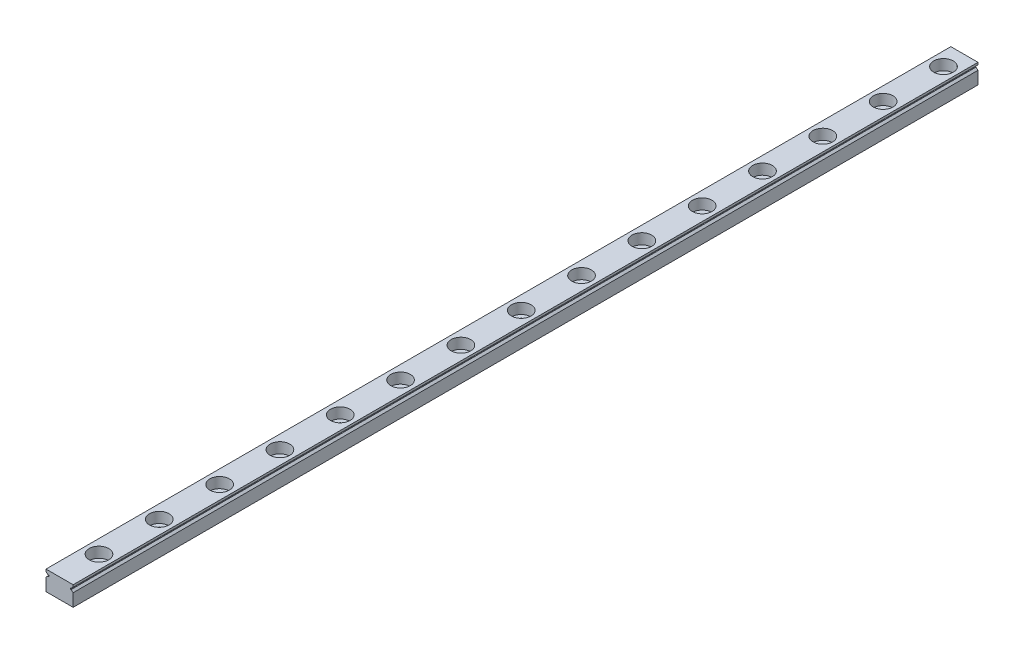
SolidWorks part; units mm, degrees
ref_plane "前视基准面" through (0, 0, 0) normal (0, 0, 1) x (1, 0, 0)
ref_plane "上视基准面" through (0, 0, 0) normal (0, 1, 0) x (1, 0, 0)
ref_plane "右视基准面" through (0, 0, 0) normal (1, 0, 0) x (0, 0, -1)
sketch "草图1" plane through (0, 0, 0) normal (0, 0, 1) x (1, 0, 0)
  line L0 (-4.5, 6.5) -> (-4.5, 0) construction
  line L1 (0, 0) -> (-9, 0)
  line L2 (0, 0) -> (0, 4.2081)
  line L3 (0, 6.5) -> (-9, 6.5)
  line L4 (-9, 0) -> (-9, 4.2081)
  line L5 (-8.0551, 4.786) -> (-8.0551, 5.1845)
  line L6 (-8.0551, 5.1845) -> (-8.3434, 5.1845)
  line L7 (-8.3434, 5.1845) -> (-9, 5.7624)
  line L8 (-8.0551, 4.786) -> (-8.3434, 4.786)
  line L9 (-8.3434, 4.786) -> (-9, 4.2081)
  line L10 (-9, 4.9853) -> (-6.6329, 4.9853) construction
  line L11 (-0.6566, 4.786) -> (0, 4.2081)
  line L12 (-0.9449, 4.786) -> (-0.6566, 4.786)
  line L13 (-0.6566, 5.1845) -> (0, 5.7624)
  line L14 (-0.9449, 5.1845) -> (-0.6566, 5.1845)
  line L15 (-0.9449, 4.786) -> (-0.9449, 5.1845)
  line L16 (0, 5.7624) -> (0, 6.5)
  line L17 (-9, 5.7624) -> (-9, 6.5)
  point P10 (-8.0551, 4.9853)
  point P22 (-0.9449, 4.9853)
  dimension "D1" = 9
  dimension "D2" = 6.5
extrude "凸台-拉伸1" add sketch "草图1" along normal blind 300
sketch "草图2" plane through (0, 6.5, 0) normal (0, 1, 0) x (1, 0, 0)
  line L0 (-4.5, 0) -> (-4.5, -10.139) construction
  line L1 (0, 0) -> (-9, 0) construction
  circle A0 centre (-4.5, -6.9424) radius 1.75
  circle A1 centre (-4.5, -26.9424) radius 1.75
  circle A2 centre (-4.5, -46.9424) radius 1.75
  circle A3 centre (-4.5, -66.9424) radius 1.75
  circle A4 centre (-4.5, -86.9424) radius 1.75
  circle A5 centre (-4.5, -106.9424) radius 1.75
  circle A6 centre (-4.5, -126.9424) radius 1.75
  circle A7 centre (-4.5, -146.9424) radius 1.75
  circle A8 centre (-4.5, -166.9424) radius 1.75
  circle A9 centre (-4.5, -186.9424) radius 1.75
  circle A10 centre (-4.5, -206.9424) radius 1.75
  circle A11 centre (-4.5, -226.9424) radius 1.75
  circle A12 centre (-4.5, -246.9424) radius 1.75
  circle A13 centre (-4.5, -266.9424) radius 1.75
  circle A14 centre (-4.5, -286.9424) radius 1.75
  circle A15 centre (-4.5, -306.9424) radius 1.75
  circle A16 centre (-4.5, -326.9424) radius 1.75
  circle A17 centre (-4.5, -346.9424) radius 1.75
  circle A18 centre (-4.5, -366.9424) radius 1.75
  circle A19 centre (-4.5, -386.9424) radius 1.75
  circle A20 centre (-4.5, -406.9424) radius 1.75
  circle A21 centre (-4.5, -426.9424) radius 1.75
  dimension "D1" = 3.5
  dimension "D2" = 22
extrude "切除-拉伸3" cut sketch "草图2" against normal blind 440
sketch "草图3" plane through (0, 6.5, 0) normal (0, 1, 0) x (1, 0, 0)
  circle A0 centre (-4.5, -6.9424) radius 3.25
  circle A1 centre (-4.5, -26.9424) radius 3.25
  circle A2 centre (-4.5, -46.9424) radius 3.25
  circle A3 centre (-4.5, -66.9424) radius 3.25
  circle A4 centre (-4.5, -86.9424) radius 3.25
  circle A5 centre (-4.5, -106.9424) radius 3.25
  circle A6 centre (-4.5, -126.9424) radius 3.25
  circle A7 centre (-4.5, -146.9424) radius 3.25
  circle A8 centre (-4.5, -166.9424) radius 3.25
  circle A9 centre (-4.5, -186.9424) radius 3.25
  circle A10 centre (-4.5, -206.9424) radius 3.25
  circle A11 centre (-4.5, -226.9424) radius 3.25
  circle A12 centre (-4.5, -246.9424) radius 3.25
  circle A13 centre (-4.5, -266.9424) radius 3.25
  circle A14 centre (-4.5, -286.9424) radius 3.25
  circle A15 centre (-4.5, -306.9424) radius 3.25
  circle A16 centre (-4.5, -326.9424) radius 3.25
  circle A17 centre (-4.5, -346.9424) radius 3.25
  circle A18 centre (-4.5, -366.9424) radius 3.25
  circle A19 centre (-4.5, -386.9424) radius 3.25
  circle A20 centre (-4.5, -406.9424) radius 3.25
  circle A21 centre (-4.5, -426.9424) radius 3.25
  circle A22 centre (-4.5, -446.9424) radius 3.25
  circle A23 centre (-4.5, -466.9424) radius 3.25
  circle A24 centre (-4.5, -486.9424) radius 3.25
  circle A25 centre (-4.5, -506.9424) radius 3.25
  circle A26 centre (-4.5, -526.9424) radius 3.25
  circle A27 centre (-4.5, -546.9424) radius 3.25
  circle A28 centre (-4.5, -566.9424) radius 3.25
  circle A29 centre (-4.5, -586.9424) radius 3.25
  circle A30 centre (-4.5, -606.9424) radius 3.25
  dimension "D1" = 6.5
  dimension "D2" = 31
extrude "切除-拉伸4" cut sketch "草图3" against normal blind 3.5
